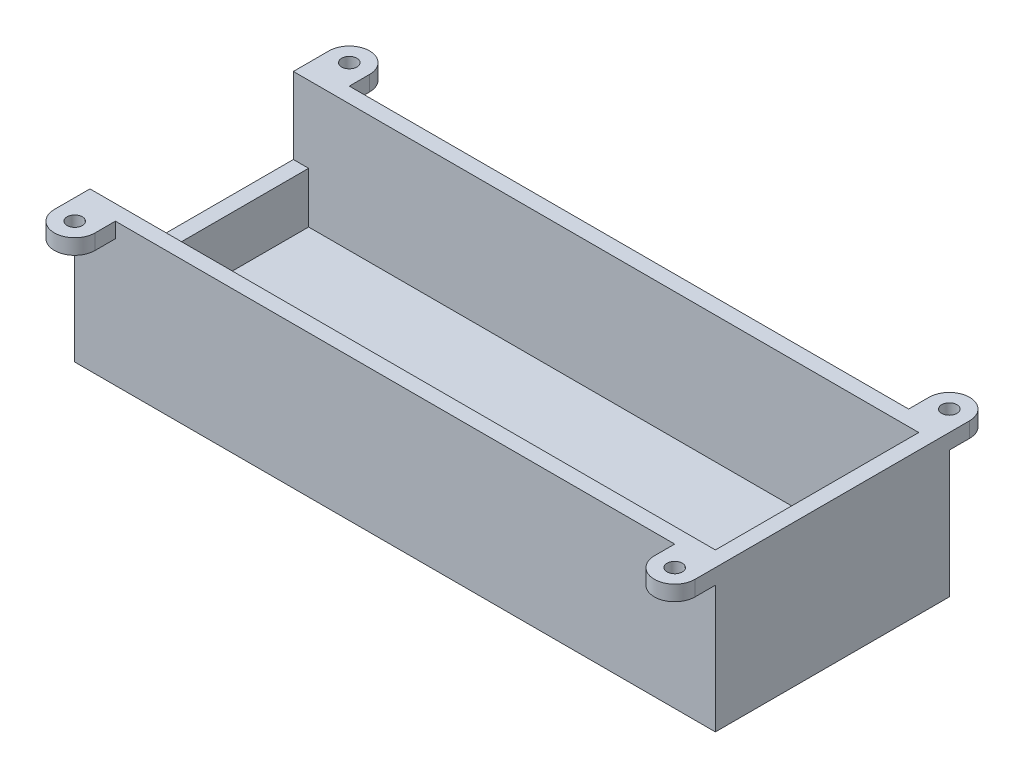
SolidWorks part; units mm, degrees
ref_plane "前视基准面" through (0, 0, 0) normal (0, 0, 1) x (1, 0, 0)
ref_plane "上视基准面" through (0, 0, 0) normal (0, 1, 0) x (1, 0, 0)
ref_plane "右视基准面" through (0, 0, 0) normal (1, 0, 0) x (0, 0, -1)
sketch "Sketch1" plane through (0, 0, 0) normal (0, 1, 0) x (1, 0, 0)
  line L1 (-63, 23) -> (63, 23)
  line L2 (-63, 23) -> (-63, -23)
  line L3 (-63, -23) -> (63, -23)
  line L4 (63, 23) -> (63, -23)
  line L5 (-63, 23) -> (63, -23) construction
  line L6 (-63, -23) -> (63, 23) construction
  point P0 (0, 0)
extrude "Extrude1" add sketch "Sketch1" along normal blind 3
sketch "Sketch2" plane through (0, 3, 0) normal (0, 1, 0) x (1, 0, 0)
  line L1 (-60, 20) -> (-60, -20)
  line L2 (-60, -20) -> (60, -20)
  line L3 (60, -20) -> (60, 20)
  line L4 (60, 20) -> (-60, 20)
  line L5 (63, -23) -> (63, 23)
  line L6 (63, 23) -> (-63, 23)
  line L7 (-63, 23) -> (-63, -23)
  line L8 (-63, -23) -> (63, -23)
  line L9 (63, -23) -> (63, 23)
  line L10 (63, 23) -> (-63, 23)
  line L11 (-63, 23) -> (-63, -23)
  line L12 (-63, -23) -> (63, -23)
  dimension "D1" = 0
  dimension "D2" = 3
extrude "Extrude2" add sketch "Sketch2" along normal blind 25
sketch "Sketch3" plane through (0, 28, 0) normal (0, 1, 0) x (1, 0, 0)
  line L0 (63, -23) -> (63, -27)
  line L1 (-63, -23) -> (-55, -23)
  line L2 (55, -27) -> (55, -23)
  line L3 (-55, -27) -> (-55, -23)
  line L4 (55, -23) -> (63, -23)
  line L5 (55, 27) -> (55, 23)
  line L6 (-55, 27) -> (-55, 23)
  line L7 (-63, -27) -> (-63, -23)
  line L8 (55, 23) -> (63, 23)
  line L9 (-63, 27) -> (-63, 23)
  line L11 (-63, 23) -> (-55, 23)
  line L12 (63, 23) -> (63, 27)
  circle A0 centre (59, 27) radius 1.5
  circle A1 centre (-59, -27) radius 1.5
  arc A2 (59, 31) -> (63, 27) centre (59, 27) cw
  arc A3 (-63, -27) -> (-59, -31) centre (-59, -27) ccw
  arc A4 (59, -31) -> (63, -27) centre (59, -27) ccw
  circle A5 centre (59, -27) radius 1.5
  arc A6 (-63, 27) -> (-59, 31) centre (-59, 27) cw
  circle A7 centre (-59, 27) radius 1.5
  arc A8 (-59, -31) -> (-55, -27) centre (-59, -27) ccw
  arc A9 (59, -31) -> (55, -27) centre (59, -27) cw
  arc A10 (-59, 31) -> (-55, 27) centre (-59, 27) cw
  arc A11 (59, 31) -> (55, 27) centre (59, 27) ccw
extrude "Extrude3" add sketch "Sketch3" against normal blind 3
sketch "Sketch4" plane through (-60, 0, 0) normal (1, 0, 0) x (0, 0, -1)
  line L0 (-20, 28) -> (-20, 3) construction
  line L1 (20, 28) -> (-20, 28)
  line L2 (20, 28) -> (20, 13)
  line L3 (20, 13) -> (-20, 13)
  line L4 (-20, 28) -> (-20, 13)
extrude "Extrude4" cut sketch "Sketch4" against normal blind 3
